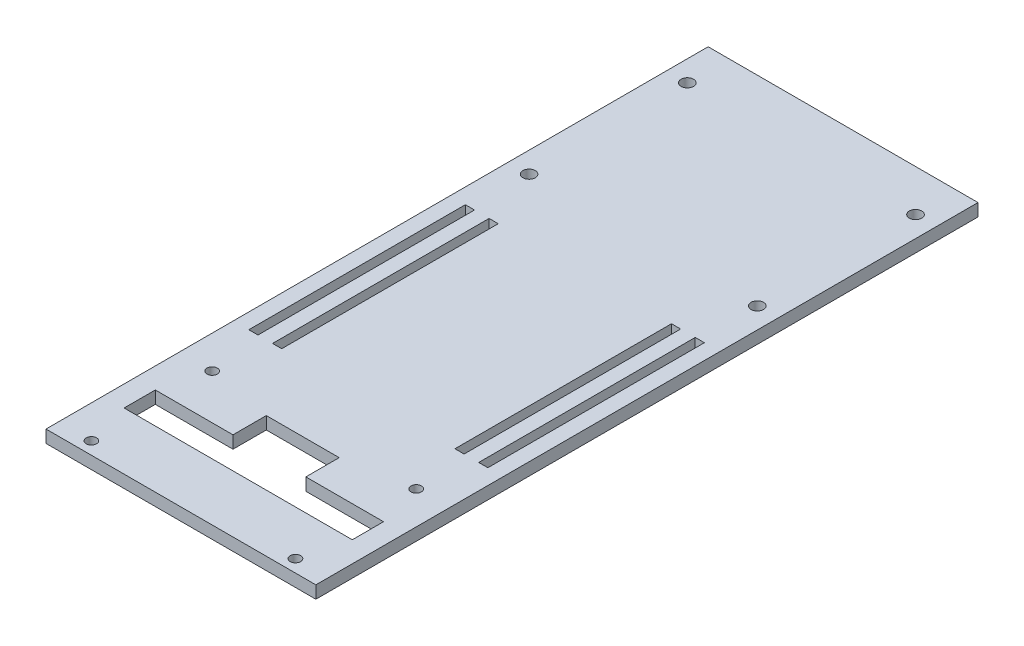
SolidWorks part; units mm, degrees
other "Markup1"
sketch "Sketch15" plane through (31.5, 14, 82.5) normal (0.3323, 0.8929, 0.3038) x (0.9376, -0.3478, -0.0034)
sketch "Sketch16" plane through (32.4, 3, 79.5) normal (0.3323, 0.8929, 0.3038) x (0.9376, -0.3478, -0.0034)
ref_plane "Front Plane" through (0, 0, 0) normal (0, 0, 1) x (1, 0, 0)
ref_plane "Top Plane" through (0, 0, 0) normal (0, 1, 0) x (1, 0, 0)
ref_plane "Right Plane" through (0, 0, 0) normal (1, 0, 0) x (0, 0, -1)
sketch "Sketch1" plane through (0, 0, 0) normal (0, 1, 0) x (1, 0, 0)
  line L0 (-27.4, 79.5) -> (-27.4, 25.5421) construction
  line L1 (-32.4, 79.5) -> (32.4, 79.5)
  line L2 (-32.4, 79.5) -> (-32.4, -79.5)
  line L3 (-32.4, -79.5) -> (32.4, -79.5)
  line L4 (32.4, 79.5) -> (32.4, -79.5)
  line L5 (-32.4, 79.5) -> (32.4, -79.5) construction
  line L6 (-32.4, -79.5) -> (32.4, 79.5) construction
  line L7 (27.4, 79.5) -> (27.4, 25.0917) construction
  circle A0 centre (-27.4, 69.5) radius 1.5
  circle A1 centre (27.4, 69.5) radius 1.5
  circle A2 centre (27.4, 31.5) radius 1.5
  circle A3 centre (-27.4, 31.5) radius 1.5
  point P0 (0, 0)
  dimension "D3" = 3
  dimension "D1" = 64.8
  dimension "D2" = 159
  dimension "D4" = 10
  dimension "D5" = 48
  dimension "D6" = 5
  dimension "D7" = 5
extrude "Boss-Extrude1" add sketch "Sketch1" along normal blind 3
sketch "Sketch4" plane through (-32.4, 0, 0) normal (-1, 0, 0) x (0, 0, 1)
  line L0 (-75, 15) -> (-75, 0) construction
  line L1 (-79.5, 0) -> (79.5, 0) construction
  line L2 (-79.5, 5) -> (-75.5, 0)
  line L3 (-79.5, 3) -> (-79.5, 0) construction
  line L4 (-75.5, 0) -> (-79.5, 0)
  line L5 (-79.5, 0) -> (-79.5, 5)
  circle A0 centre (-75, 9) radius 1.9
  dimension "D1" = 3.8
  dimension "D2" = 9
  dimension "D3" = 4
  dimension "D4" = 5
extrude "Cut-Extrude2" [suppressed] cut sketch "Sketch4" against normal through all both and the other way through all
sketch "Sketch7" plane through (0, 3, 0) normal (0, 1, 0) x (1, 0, 0)
  line L0 (-28.7, -8.5) -> (-32.4, -8.5) construction
  line L1 (-28.7, 17.5) -> (-26.5, 17.5)
  line L2 (-28.7, 17.5) -> (-28.7, -34.5)
  line L3 (-28.7, -34.5) -> (-26.5, -34.5)
  line L4 (-26.5, 17.5) -> (-26.5, -34.5)
  line L5 (26.5, 17.5) -> (28.7, 17.5)
  line L6 (26.5, 17.5) -> (26.5, -34.5)
  line L7 (26.5, -34.5) -> (28.7, -34.5)
  line L8 (28.7, 17.5) -> (28.7, -34.5)
  line L9 (-32.4, 79.5) -> (-32.4, -79.5) construction
  line L10 (28.7, -8.5) -> (32.4, -8.5) construction
  line L11 (32.4, -79.5) -> (32.4, 79.5) construction
  line L12 (-32.4, -79.5) -> (32.4, -79.5) construction
  line L14 (-23, 17.5) -> (-20.8, 17.5)
  line L15 (-23, 17.5) -> (-23, -34.5)
  line L16 (-23, -34.5) -> (-20.8, -34.5)
  line L17 (-20.8, 17.5) -> (-20.8, -34.5)
  line L18 (23, 17.5) -> (20.8, 17.5)
  line L19 (23, 17.5) -> (23, -34.5)
  line L20 (23, -34.5) -> (20.8, -34.5)
  line L21 (20.8, 17.5) -> (20.8, -34.5)
  dimension "D1" = 53
  dimension "D2" = 2.2
  dimension "D3" = 52
  dimension "D4" = 45
  dimension "D5" = 3.5
  dimension "D6" = 2.2
  dimension "D7" = 3.5
extrude "Cut-Extrude4" cut sketch "Sketch7" against normal through all
sketch "Sketch9" plane through (0, 3, 0) normal (0, 1, 0) x (1, 0, 0)
  line L0 (32.4, -79.5) -> (32.4, 79.5) construction
  line L1 (-27.4, -65.75) -> (27.4, -65.75)
  line L2 (-27.4, -65.75) -> (-27.4, -58.25)
  line L3 (-27.4, -58.25) -> (-8.75, -58.25)
  line L4 (27.4, -65.75) -> (27.4, -58.25)
  line L5 (-32.4, 79.5) -> (-32.4, -79.5) construction
  line L6 (-32.4, -79.5) -> (32.4, -79.5) construction
  line L7 (8.75, -58.25) -> (27.4, -58.25)
  line L9 (-8.75, -58.25) -> (-8.75, -50.25)
  line L10 (-8.75, -50.25) -> (8.75, -50.25)
  line L11 (8.75, -58.25) -> (8.75, -50.25)
  point P14 (0, -50.25)
  point P15 (0, -65.75)
  dimension "D1" = 5
  dimension "D2" = 5
  dimension "D3" = 13.75
  dimension "D4" = 7.5
  dimension "D5" = 17.5
  dimension "D6" = 15.5
extrude "Cut-Extrude6" cut sketch "Sketch9" against normal through all
sketch "Sketch12" plane through (0, 3, 0) normal (0, 1, 0) x (1, 0, 0)
  line L0 (-32.4, -76.5) -> (32.4, -76.5) construction
  line L1 (-32.4, 79.5) -> (-32.4, -79.5) construction
  line L2 (32.4, -79.5) -> (32.4, 79.5) construction
  line L3 (-24.5, -79.5) -> (-24.5, -47.5) construction
  line L4 (-32.4, -79.5) -> (32.4, -79.5) construction
  line L5 (24.5, -79.5) -> (24.5, -47.5) construction
  line L6 (-24.5, -47.5) -> (-32.4, -47.5) construction
  line L7 (24.5, -47.5) -> (32.4, -47.5) construction
  circle A0 centre (-24.5, -47.5) radius 1.25
  circle A1 centre (24.5, -47.5) radius 1.25
  circle A2 centre (24.5, -76.5) radius 1.25
  circle A3 centre (-24.5, -76.5) radius 1.25
  dimension "D3" = 2.5
  dimension "D1" = 3
  dimension "D2" = 49
  dimension "D4" = 29
extrude "Cut-Extrude8" cut sketch "Sketch12" against normal blind 10
